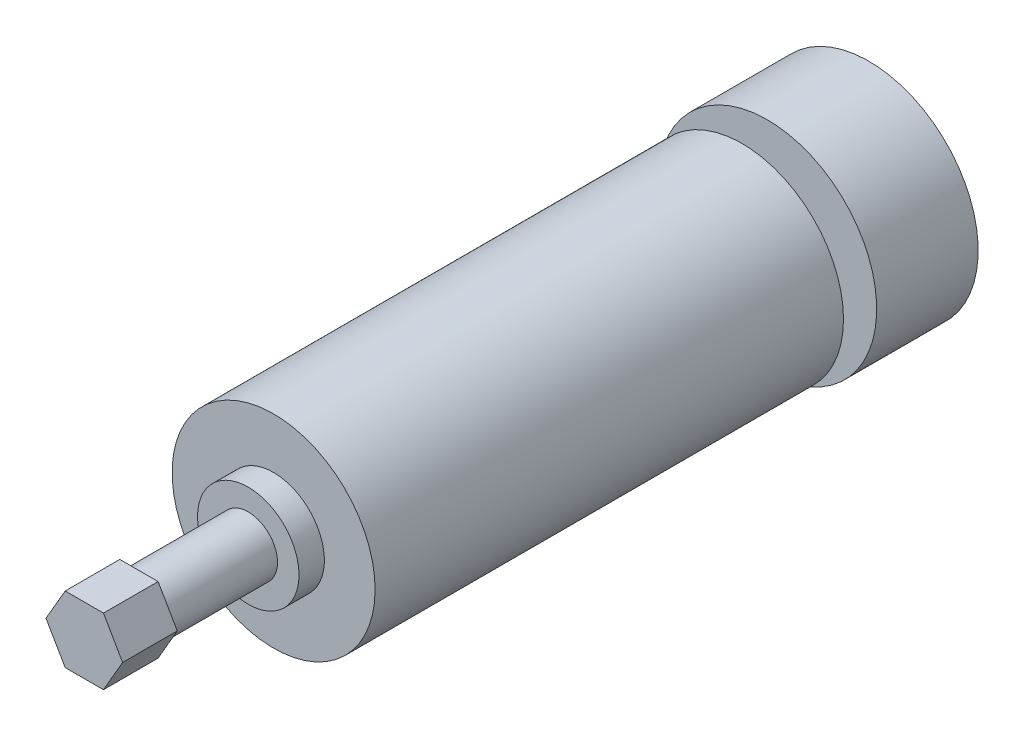
SolidWorks part; units mm, degrees
ref_plane "Plan de face" through (0, 0, 0) normal (0, 0, 1) x (1, 0, 0)
ref_plane "Plan de dessus" through (0, 0, 0) normal (0, 1, 0) x (1, 0, 0)
ref_plane "Plan de droite" through (0, 0, 0) normal (1, 0, 0) x (0, 0, -1)
sketch "Esquisse1" plane through (0, 0, 0) normal (0, 0, 1) x (1, 0, 0)
  circle A0 centre (0, 0) radius 26
  dimension "D1" = 52
extrude "Boss.-Extru.1" add sketch "Esquisse1" along normal blind 120
sketch "Esquisse2" plane through (0, 0, 120) normal (0, 0, 1) x (1, 0, 0)
  circle A0 centre (0, 0) radius 13
  dimension "D1" = 26
extrude "Boss.-Extru.2" add sketch "Esquisse2" along normal blind 6.5
sketch "Esquisse3" plane through (0, 0, 0) normal (0, 0, -1) x (-1, 0, 0)
  circle A0 centre (0, 0) radius 13
  dimension "D1" = 26
extrude "Boss.-Extru.3" add sketch "Esquisse3" along normal blind 6.5
sketch "Esquisse4" plane through (0, 0, 126.5) normal (0, 0, 1) x (1, 0, 0)
  circle A0 centre (0, 0) radius 7.5
  dimension "D1" = 15
extrude "Boss.-Extru.4" add sketch "Esquisse4" along normal blind 28
sketch "Esquisse5" plane through (0, 0, 154.5) normal (0, 0, 1) x (1, 0, 0)
  line L1 (9.815, 0) -> (4.9075, 8.5)
  line L2 (4.9075, 8.5) -> (-4.9075, 8.5)
  line L3 (-4.9075, 8.5) -> (-9.815, 0)
  line L4 (-9.815, 0) -> (-4.9075, -8.5)
  line L5 (-4.9075, -8.5) -> (4.9075, -8.5)
  line L6 (4.9075, -8.5) -> (9.815, 0)
  circle A0 centre (0, 0) radius 8.5 construction
  dimension "D1" = 17
extrude "Boss.-Extru.5" add sketch "Esquisse5" along normal blind 14
sketch "Esquisse6" plane through (0, 0, -6.5) normal (0, 0, -1) x (-1, 0, 0)
  circle A0 centre (0, 0) radius 28
  dimension "D1" = 56
extrude "Boss.-Extru.6" add sketch "Esquisse6" along normal blind 26
